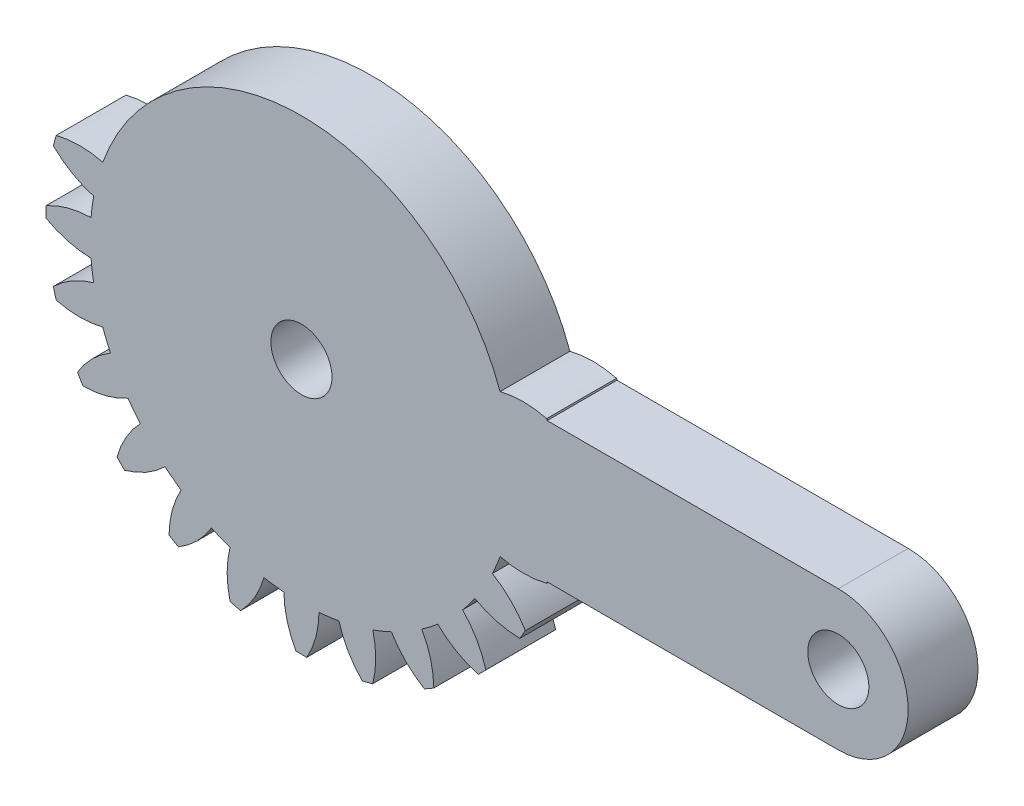
SolidWorks part; units mm, degrees
ref_plane "Front Plane" through (0, 0, 0) normal (0, 0, 1) x (1, 0, 0)
ref_plane "Top Plane" through (0, 0, 0) normal (0, 1, 0) x (1, 0, 0)
ref_plane "Right Plane" through (0, 0, 0) normal (1, 0, 0) x (0, 0, -1)
sketch "Sketch1" plane through (0, 0, 0) normal (0, 0, 1) x (1, 0, 0)
  line L0 (0, 0) -> (0, 14.63) construction
  line L1 (0, 0) -> (32.007, 0) construction
  line L2 (11.4091, 4) -> (30.75, 4)
  line L3 (11.4091, -4) -> (30.75, -4)
  circle A0 centre (0, 0) radius 12.09
  circle A1 centre (0, 0) radius 14.63
  circle A2 centre (0, 0) radius 1.75
  arc A3 (0.31, 14.6267) -> (1.0062, 12.0481) centre (-4.3933, 11.9736) cw
  arc A4 (-0.31, 14.6267) -> (-1.0062, 12.0481) centre (4.3933, 11.9736) ccw
  arc A5 (3.4862, 14.2086) -> (2.1464, 11.898) centre (7.3426, 10.4285) ccw
  arc A6 (4.0851, 14.0481) -> (4.0902, 11.3771) centre (-1.1446, 12.7027) cw
  arc A7 (7.0449, 12.8221) -> (5.1526, 10.937) centre (9.7915, 8.1728) ccw
  arc A8 (7.5818, 12.5121) -> (6.8954, 9.9308) centre (2.1821, 12.5661) cw
  arc A9 (10.1234, 10.5619) -> (7.8078, 9.2308) centre (11.5731, 5.3601) ccw
  arc A10 (10.5619, 10.1234) -> (9.2308, 7.8078) centre (5.3601, 11.5731) cw
  arc A11 (12.5121, 7.5818) -> (9.9308, 6.8954) centre (12.5661, 2.1821) ccw
  arc A12 (12.8221, 7.0449) -> (10.937, 5.1526) centre (8.1728, 9.7915) cw
  arc A13 (14.0481, 4.0851) -> (11.3771, 4.0902) centre (12.7027, -1.1446) ccw
  arc A14 (14.2086, 3.4862) -> (11.898, 2.1464) centre (10.4285, 7.3426) cw
  arc A15 (14.6267, 0.31) -> (12.0481, 1.0062) centre (11.9736, -4.3933) ccw
  arc A16 (14.6267, -0.31) -> (12.0481, -1.0062) centre (11.9736, 4.3933) cw
  arc A17 (14.2086, -3.4862) -> (11.898, -2.1464) centre (10.4285, -7.3426) ccw
  arc A18 (14.0481, -4.0851) -> (11.3771, -4.0902) centre (12.7027, 1.1446) cw
  arc A19 (12.8221, -7.0449) -> (10.937, -5.1526) centre (8.1728, -9.7915) ccw
  arc A20 (12.5121, -7.5818) -> (9.9308, -6.8954) centre (12.5661, -2.1821) cw
  arc A21 (10.5619, -10.1234) -> (9.2308, -7.8078) centre (5.3601, -11.5731) ccw
  arc A22 (10.1234, -10.5619) -> (7.8078, -9.2308) centre (11.5731, -5.3601) cw
  arc A23 (7.5818, -12.5121) -> (6.8954, -9.9308) centre (2.1821, -12.5661) ccw
  arc A24 (7.0449, -12.8221) -> (5.1526, -10.937) centre (9.7915, -8.1728) cw
  arc A25 (4.0851, -14.0481) -> (4.0902, -11.3771) centre (-1.1446, -12.7027) ccw
  arc A26 (3.4862, -14.2086) -> (2.1464, -11.898) centre (7.3426, -10.4285) cw
  arc A27 (0.31, -14.6267) -> (1.0062, -12.0481) centre (-4.3933, -11.9736) ccw
  arc A28 (-0.31, -14.6267) -> (-1.0062, -12.0481) centre (4.3933, -11.9736) cw
  arc A29 (-3.4862, -14.2086) -> (-2.1464, -11.898) centre (-7.3426, -10.4285) ccw
  arc A30 (-4.0851, -14.0481) -> (-4.0902, -11.3771) centre (1.1446, -12.7027) cw
  arc A31 (-7.0449, -12.8221) -> (-5.1526, -10.937) centre (-9.7915, -8.1728) ccw
  arc A32 (-7.5818, -12.5121) -> (-6.8954, -9.9308) centre (-2.1821, -12.5661) cw
  arc A33 (-10.1234, -10.5619) -> (-7.8078, -9.2308) centre (-11.5731, -5.3601) ccw
  arc A34 (-10.5619, -10.1234) -> (-9.2308, -7.8078) centre (-5.3601, -11.5731) cw
  arc A35 (-12.5121, -7.5818) -> (-9.9308, -6.8954) centre (-12.5661, -2.1821) ccw
  arc A36 (-12.8221, -7.0449) -> (-10.937, -5.1526) centre (-8.1728, -9.7915) cw
  arc A37 (-14.0481, -4.0851) -> (-11.3771, -4.0902) centre (-12.7027, 1.1446) ccw
  arc A38 (-14.2086, -3.4862) -> (-11.898, -2.1464) centre (-10.4285, -7.3426) cw
  arc A39 (-14.6267, -0.31) -> (-12.0481, -1.0062) centre (-11.9736, 4.3933) ccw
  arc A40 (-14.6267, 0.31) -> (-12.0481, 1.0062) centre (-11.9736, -4.3933) cw
  arc A41 (-14.2086, 3.4862) -> (-11.898, 2.1464) centre (-10.4285, 7.3426) ccw
  arc A42 (-14.0481, 4.0851) -> (-11.3771, 4.0902) centre (-12.7027, -1.1446) cw
  arc A43 (-12.8221, 7.0449) -> (-10.937, 5.1526) centre (-8.1728, 9.7915) ccw
  arc A44 (-12.5121, 7.5818) -> (-9.9308, 6.8954) centre (-12.5661, 2.1821) cw
  arc A45 (-10.5619, 10.1234) -> (-9.2308, 7.8078) centre (-5.3601, 11.5731) ccw
  arc A46 (-10.1234, 10.5619) -> (-7.8078, 9.2308) centre (-11.5731, 5.3601) cw
  arc A47 (-7.5818, 12.5121) -> (-6.8954, 9.9308) centre (-2.1821, 12.5661) ccw
  arc A48 (-7.0449, 12.8221) -> (-5.1526, 10.937) centre (-9.7915, 8.1728) cw
  arc A49 (-4.0851, 14.0481) -> (-4.0902, 11.3771) centre (1.1446, 12.7027) ccw
  arc A50 (-3.4862, 14.2086) -> (-2.1464, 11.898) centre (-7.3426, 10.4285) cw
  arc A51 (30.75, 4) -> (30.75, -4) centre (30.75, 0) cw
  circle A52 centre (30.75, 0) radius 1.75
  point P2 (-30.2306, -0.1946)
  point P156 (-0.3594, -0.3009)
  point P157 (0, 0)
  point P158 (13.8364, -4.7531)
  point P159 (14.0249, -4.1348)
  point P161 (-53.8753, -8.6052)
  point P163 (14.0249, -4.1348)
  point P164 (0, 0)
  point P165 (-31.6903, 0.6414)
  dimension "D1" = 3.5
  dimension "D2" = 24.18
  dimension "D3" = 29.26
  dimension "D6" = 5.4
  dimension "D7" = 24
  dimension "D8" = 30.75
  dimension "D9" = 4
  dimension "D10" = 3.5
  dimension "D4" = 0.62
  dimension "D11" = 1.15
extrude "Boss-Extrude1" add sketch "Sketch1" along normal blind 4 contours A0 | A51 L2 A1 L3 A52 | A18 A1 L3 A0 | A16 A1 A15 A0 | A15 A1 A14 A0 | A14 A1 L2 A0 | A1 A13 A0 L2 | A1 A17 A0 L3 | A17 A1 A16 A0 | A20 A1 A19 A0 | A22 A1 A21 A0 | A24 A1 A23 A0 | A26 A1 A25 A0 | A28 A1 A27 A0 | A30 A1 A29 A0 | A32 A1 A31 A0 | A34 A1 A33 A0 | A36 A1 A35 A0 | A38 A1 A37 A0 | A40 A1 A39 A0 | A42 A1 A41 A0
